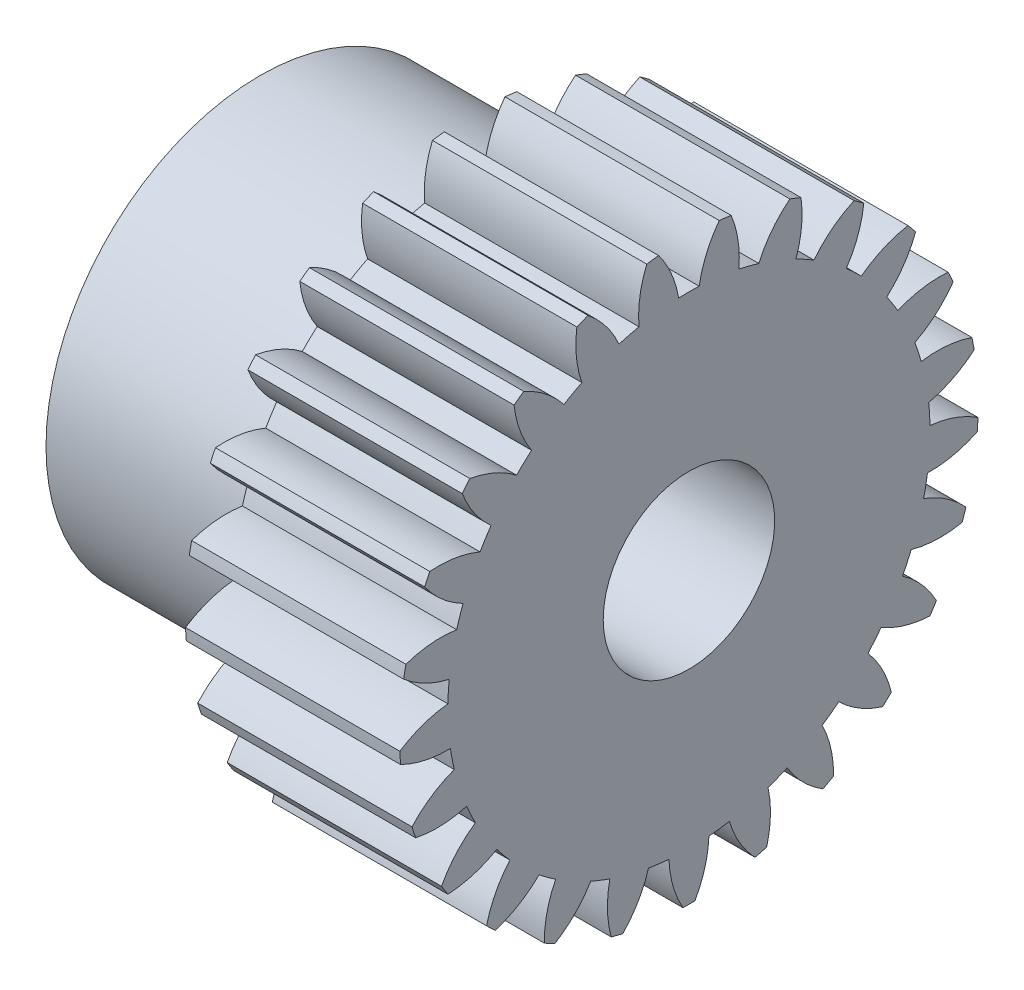
SolidWorks part; units mm, degrees
ref_plane "Plane1" through (0, 0, 0) normal (0, 0, 1) x (1, 0, 0)
ref_plane "Plane2" through (0, 0, 0) normal (0, 1, 0) x (1, 0, 0)
ref_plane "Plane3" through (0, 0, 0) normal (1, 0, 0) x (0, 0, -1)
sketch "HoldingSke" plane through (0, 0, 0) normal (0, 1, 0) x (1, 0, 0)
  line L0 (0, 0) -> (0.9063, -0.4226)
  line L1 (-15, 0) -> (100, 0) construction
  line L2 (0, 0) -> (-2.1039, 2.3779)
  line L3 (0, 0) -> (-11.863, 4.5341)
  line L4 (0, 0) -> (7.8269, 3.6497)
  line L5 (0, 0) -> (-18.7391, -6.9891)
  line L6 (0, 0) -> (-8.2896, -5.593)
  line L7 (-2.1039, 2.3779) -> (2.2011, 21.9091)
  line L8 (-76.2, 54.61) -> (-74.8, 54.61)
  line L9 (-71.009, 38.7566) -> (-53.1078, 45.2721)
  line L10 (-76.2, 71.12) -> (104.1128, 71.12)
  line L11 (0, 0) -> (-10, 0)
  line L12 (-76.2, 101.6) -> (-76.162, 101.6)
  line L13 (24.9733, 27.94) -> (52.9518, 28.4284)
  line L14 (24.9733, 27.94) -> (24.9743, 27.94)
  line L15 (24.9733, 27.94) -> (100.4006, 29.5858)
  line L16 (-63.627, -1) -> (-12.827, -1)
  circle A0 centre (0, 0) radius 4
  circle A1 centre (0, 0) radius 10
  circle A2 centre (0, 0) radius 10
  circle A3 centre (0, 0) radius 4
  dimension "Bore" = 8
  dimension "MBD" = 8
  dimension "Pitch" = 1
  dimension "T_dim" = 1.4
  dimension "Ap" = 20
  dimension "H" = 19.05
  dimension "Pitch_radius" = 180.3128
  dimension "Backlash" = 0.038
  dimension "Addendum_fac" = 1
  dimension "Dedendum_fac" = 1.25
  dimension "Clearance_fac" = 0.25
  dimension "Dedendum_add" = 0.001
  dimension "Module" = 1
sketch "BasProSke" plane through (0, 0, 0) normal (0, 1, 0) x (1, 0, 0)
  line L0 (-10, 0) -> (60, 0) construction
  line L1 (0, 0) -> (0, 13.5)
  line L2 (0, 0) -> (10, 0)
  line L3 (10, 0) -> (10, 13.5)
  line L4 (10, 13.5) -> (0, 13.5)
revolve "Base-Revolve" add sketch "BasProSke" angle 360 about L0
sketch "TooCutSke" plane through (0, 0, 0) normal (1, 0, 0) x (0, 0, -1)
  line L1 (0, 0) -> (0, 107) construction
  line L2 (0, 0) -> (-0.8514, 12.471) construction
  line L3 (0, 0) -> (-3.1282, 24.7619) construction
  line L4 (-0.8514, 12.471) -> (-1.5641, 12.3809) construction
  arc A0 (0.4801, 11.2388) -> (-0.4801, 11.2388) centre (0, 0) ccw
  arc A1 (1.4322, 13.4494) -> (-1.4322, 13.4494) centre (0, 0) ccw
  circle A2 centre (0, 0) radius 12.5 construction
  circle A3 centre (0, 0) radius 11.7462 construction
  arc A4 (-0.4801, 11.2388) -> (-1.4322, 13.4494) centre (-5.4133, 10.4244) ccw
  arc A5 (1.4322, 13.4494) -> (0.4801, 11.2388) centre (5.4133, 10.4244) ccw
extrude "ToothCut" cut sketch "TooCutSke" along normal through all
fillet "Breaks" [suppressed] radius 0.02
fillet "RootFillets" [suppressed] radius 0.251
pattern_circular "TeethCuts" count 25 every 14.4 about axis through (-10, 0, 0) along (1, 0, 0) of "ToothCut", "RootFillets", "Breaks"
sketch "HubNeaOneSke" plane through (0, 0, 0) normal (-1, 0, 0) x (0, 0, 1)
  circle A0 centre (0, 0) radius 10
extrude "HubNearOne" add sketch "HubNeaOneSke" along normal blind 10.0001
sketch "HubNeaBotSke" plane through (0, 0, 0) normal (-1, 0, 0) x (0, 0, 1)
  circle A0 centre (0, 0) radius 10
extrude "HubNearBoth" [suppressed] add sketch "HubNeaBotSke" along normal blind 5
ref_plane "FarPln" through (10, 0, 0) normal (1, 0, 0) x (0, 0, -1)
sketch "HubFarSke" plane through (10, 0, 0) normal (1, 0, 0) x (0, 0, -1)
  circle A0 centre (0, 0) radius 10
extrude "HubFar" [suppressed] add sketch "HubFarSke" along normal blind 5
sketch "BorSke" plane through (0, 0, 0) normal (1, 0, 0) x (0, 0, -1)
  circle A0 centre (0, 0) radius 4
  dimension "Diameter" = 8
extrude "Bore" cut sketch "BorSke" along normal mid plane 40.0001
sketch "KeySke" plane through (0, 0, 0) normal (1, 0, 0) x (0, 0, -1)
  line L0 (-1.5, 0) -> (-1.5, 5.4)
  line L1 (-1.5, 5.4) -> (1.5, 5.4)
  line L2 (1.5, 5.4) -> (1.5, 0)
  line L3 (0, 0) -> (0, 34) construction
  line L4 (-1.5, 0) -> (1.5, 0)
  dimension "Offset" = 5.4
  dimension "Width" = 3
extrude "Keyway" [suppressed] cut sketch "KeySke" along normal mid plane 40.0001
pattern_circular "Keyway2" [suppressed] count 2 every 90 about axis through (-10, 0, 0) along (1, 0, 0)
equation "' \"Module@HoldingSke\" = 6.35"
equation "' \"Num_teeth@HoldingSke\" = 12"
equation "' \"Ap@HoldingSke\" =  20"
equation "' \"Ap@HoldingSke\" = 20"
equation "' \"Width@HoldingSke\" = 0.5 * 25.4"
equation "' \"Hub_dia@HoldingSke\"= 1 * 25.4"
equation "' \"Hub_dia@HoldingSke\" = 1 * 25.4"
equation "' \"Overall_len@HoldingSke\" = 1.0 * 25.4"
equation "' \"Bore@HoldingSke\" = 0.75 * 25.4"
equation "' \"T_dim@HoldingSke\" = 0.1 * 25.4"
equation "' \"Width@KeySke\" = 0.25 * 25.4"
equation "' \"Show_teeth@HoldingSke\" = 13"
equation "' \"Backlash@HoldingSke\" = 0.009 * 25.4"
equation "' \"Addendum_fac@HoldingSke\" = 1.0"
equation "' \"Dedendum_fac@HoldingSke\" = 1.25"
equation "' \"Dedendum_add@HoldingSke\" = 0.00005 * 25.4"
equation "' \"Clearance_fac@HoldingSke\" = 0.25"
equation "\"Pitch@HoldingSke\" = 1 / \"Module@HoldingSke\""
equation "\"Overcut_dia@TooCutSke\" = (\"Num_teeth@HoldingSke\" + 2 * \"Addendum_fac@HoldingSke\") / \"Pitch@HoldingSke\" + 0.002 * 25.4"
equation "\"Pitch_dia@TooCutSke\" = \"Num_teeth@HoldingSke\" / \"Pitch@HoldingSke\""
equation "\"Base_dia@TooCutSke\" = \"Num_teeth@HoldingSke\" / \"Pitch@HoldingSke\" * cos((\"Ap@HoldingSke\"  * 3.14159265 / 180))"
equation "\"Root_dia@TooCutSke\" = (\"Num_teeth@HoldingSke\" + 2) / \"Pitch@HoldingSke\" - 2 * (\"Addendum_fac@HoldingSke\" + \"Dedendum_fac@HoldingSke\") / \"Pitch@HoldingSke\" - \"Dedendum_add@HoldingSke\" * 2"
equation "\"Half_ang@TooCutSke\" = 180 / \"Num_teeth@HoldingSke\""
equation "\"Half_CT@TooCutSke\" = \"Num_teeth@HoldingSke\" / \"Pitch@HoldingSke\" * sin((3.14159265 / 2 / \"Num_teeth@HoldingSke\")) / 2 - 7 * \"Backlash@HoldingSke\" / 4"
equation "\"Flank_rad@TooCutSke\" = \"Num_teeth@HoldingSke\" / \"Pitch@HoldingSke\" / 5"
equation "\"Radius@RootFillets\" = \"Clearance_fac@HoldingSke\" / \"Pitch@HoldingSke\" + \"Dedendum_add@HoldingSke\""
equation "\"Break_rad@Breaks\" = 0.02 / \"Pitch@HoldingSke\""
equation "\"Thickness@HoldingSke\" = \"Width@HoldingSke\""
equation "\"OAL@HoldingSke\" = \"Thickness@HoldingSke\""
equation "\"MHD@HoldingSke\" = (\"Num_teeth@HoldingSke\" + 2) / \"Pitch@HoldingSke\" - 2 * (\"Addendum_fac@HoldingSke\" + \"Dedendum_fac@HoldingSke\")  / \"Pitch@HoldingSke\" - \"Dedendum_add@HoldingSke\" * 2"
equation "\"MBD@HoldingSke\" = (\"Num_teeth@HoldingSke\" + 2) / \"Pitch@HoldingSke\" - 2 * (\"Addendum_fac@HoldingSke\" + \"Dedendum_fac@HoldingSke\")  / \"Pitch@HoldingSke\" - \"Dedendum_add@HoldingSke\" * 2 - 0.002 * 25.4"
equation "\"MHD@HoldingSke\" = ((sgn( \"MHD@HoldingSke\" - \"Hub_dia@HoldingSke\" )-1)*( \"MHD@HoldingSke\" - \"Hub_dia@HoldingSke\" ))/-2+ \"Hub_dia@HoldingSke\""
equation "\"MBD@HoldingSke\" = ((sgn( \"MBD@HoldingSke\" - \"Bore@HoldingSke\" )-1)*( \"MBD@HoldingSke\" - \"Bore@HoldingSke\" ))/-2+ \"Bore@HoldingSke\""
equation "\"OAL@HoldingSke\" = ((sgn( \"OAL@HoldingSke\" - \"Overall_len@HoldingSke\" )+1)*( \"OAL@HoldingSke\" - \"Overall_len@HoldingSke\" ))/2 + \"Overall_len@HoldingSke\" + 0.000002 * 25.4"
equation "\"Num_teeth@TeethCuts\" = int( \"Show_teeth@HoldingSke\" ) + 1"
equation "\"Num_teeth@TeethCuts\" = ((sgn( \"Num_teeth@TeethCuts\" - \"Num_teeth@HoldingSke\" )-1)*( \"Num_teeth@TeethCuts\" - \"Num_teeth@HoldingSke\" ))/-2+ \"Num_teeth@HoldingSke\""
equation "\"Num_teeth@TeethCuts\" = ((sgn( \"Num_teeth@TeethCuts\" - 2.0)+1)*( \"Num_teeth@TeethCuts\" - 2.0))/2 +2.0"
equation "\"Angle@TeethCuts\" = 360.0 / \"Num_teeth@HoldingSke\""
equation "\"Diameter@BasProSke\" = (\"Num_teeth@HoldingSke\" + 2 * \"Addendum_fac@HoldingSke\") / \"Pitch@HoldingSke\""
equation "\"Thickness@BasProSke\"  = \"Thickness@HoldingSke\""
equation "' \"Fillet_rad@BasProSke\" =  \"Thickness@HoldingSke\" * 0.05"
equation "' \"Fillet_rad@BasProSke\" = \"Thickness@HoldingSke\" * 0.05"
equation "\"MHD@HoldingSke\" = ((sgn( \"MHD@HoldingSke\" - \"Root_dia@TooCutSke\" )-1)*( \"MHD@HoldingSke\" - \"Root_dia@TooCutSke\" ))/-2+ \"Root_dia@TooCutSke\""
equation "\"Diameter@HubNeaOneSke\" = \"MHD@HoldingSke\""
equation "\"Length@HubNearOne\" = \"OAL@HoldingSke\" - \"Thickness@BasProSke\""
equation "\"Diameter@HubNeaBotSke\" = \"MHD@HoldingSke\""
equation "\"Length@HubNearBoth\" = ( \"OAL@HoldingSke\" - \"Thickness@BasProSke\" ) / 2.0"
equation "\"Thickness@FarPln\" = \"Thickness@BasProSke\""
equation "\"Diameter@HubFarSke\" = \"MHD@HoldingSke\""
equation "\"Length@HubFar\" = ( \"OAL@HoldingSke\" - \"Thickness@BasProSke\" ) / 2.0"
equation "\"Diameter@BorSke\" = \"MBD@HoldingSke\""
equation "\"D1@Bore\" = \"OAL@HoldingSke\" * 2.0"
equation "\"D1@Keyway\" = \"OAL@HoldingSke\" * 2.0"
equation "\"Offset@KeySke\" = \"T_dim@HoldingSke\" + \"MBD@HoldingSke\" / 2.0"
